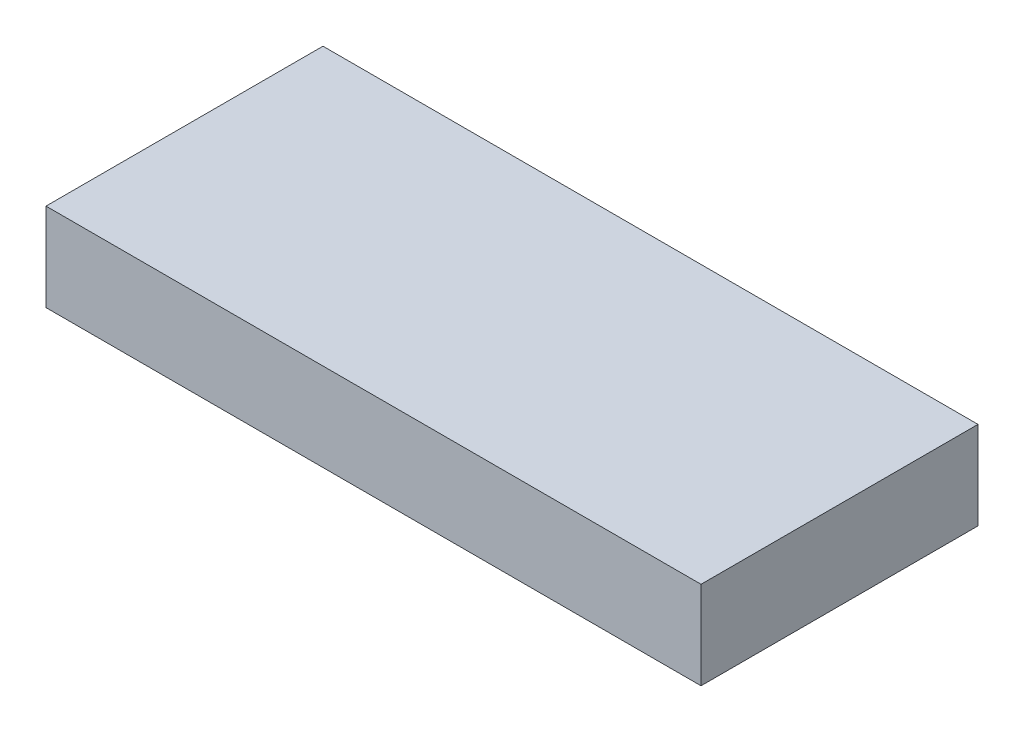
SolidWorks part; units mm, degrees
ref_plane "Front Plane" through (0, 0, 0) normal (0, 0, 1) x (1, 0, 0)
ref_plane "Top Plane" through (0, 0, 0) normal (0, 1, 0) x (1, 0, 0)
ref_plane "Right Plane" through (0, 0, 0) normal (1, 0, 0) x (0, 0, -1)
sketch "Sketch1" plane through (0, 0, 0) normal (0, 1, 0) x (1, 0, 0)
  line L1 (0, 0) -> (47.3, 0)
  line L2 (0, 0) -> (0, 20)
  line L3 (0, 20) -> (47.3, 20)
  line L4 (47.3, 0) -> (47.3, 20)
  dimension "D1" = 47.3
  dimension "D2" = 20
extrude "Boss-Extrude1" add sketch "Sketch1" along normal blind 6.35
